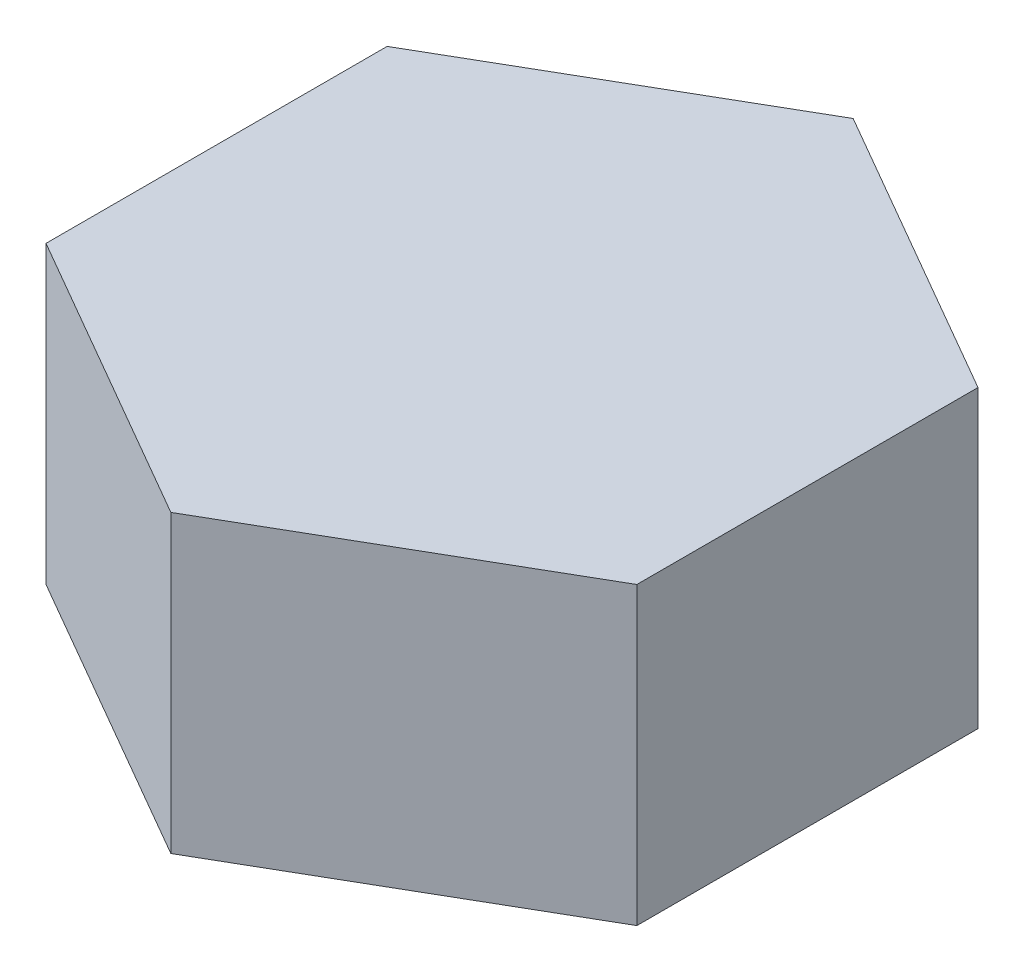
SolidWorks part; units mm, degrees
ref_plane "Front Plane" through (0, 0, 0) normal (0, 0, 1) x (1, 0, 0)
ref_plane "Top Plane" through (0, 0, 0) normal (0, 1, 0) x (1, 0, 0)
ref_plane "Right Plane" through (0, 0, 0) normal (1, 0, 0) x (0, 0, -1)
sketch "Sketch2" plane through (0, 0, 0) normal (0, 1, 0) x (1, 0, 0)
  line L1 (50.8, 29.3294) -> (0, 58.6588)
  line L2 (0, 58.6588) -> (-50.8, 29.3294)
  line L3 (-50.8, 29.3294) -> (-50.8, -29.3294)
  line L4 (-50.8, -29.3294) -> (0, -58.6588)
  line L5 (0, -58.6588) -> (50.8, -29.3294)
  line L6 (50.8, -29.3294) -> (50.8, 29.3294)
  circle A0 centre (0, 0) radius 50.8 construction
extrude "Boss-Extrude2" add sketch "Sketch2" along normal blind 50.8
sketch "Sketch4" plane through (0, 50.8, 0) normal (0, 1, 0) x (1, 0, 0)
  line L0 (0, 58.6588) -> (0, -58.6588)
ref_plane "Plane1" through (0, 0, 0) normal (-1, 0, 0) x (0, 0, 1)
sketch "Sketch13" plane through (0, 50.8, 0) normal (0, 1, 0) x (1, 0, 0)
  line L0 (-50.8, 0) -> (50.8, 0)
  line L1 (-50.8, 29.3294) -> (-50.8, -29.3294) construction
  line L2 (50.8, -29.3294) -> (50.8, 29.3294) construction
  circle A0 centre (0, 0) radius 47.3756
sketch "Sketch14" plane through (0, 0, 0) normal (0, -1, 0) x (-1, 0, 0)
  line L0 (0, -58.6588) -> (0, 58.6588)
sketch "Sketch15" plane through (0, 0, 0) normal (-1, 0, 0) x (0, 0, 1)
  line L0 (-58.6588, 50.8) -> (58.6588, 50.8) construction
  arc A0 (47.2401, 50.8) -> (-47.4979, 50.8) centre (-0.1289, 47.4847) cw
sketch3d "3DSketch2"
  line L0 (50.8, 50.8, 0) -> (-50.8, 50.8, 0) construction
  arc A0 (-46.3664, 50.8, 0) -> (46.3664, 50.8, 0) centre (0, 46.5598, 0) cw
  circle A1 centre (0, 50.8, 0) radius 46.3664 construction
  point P2 (0, 46.5598, 46.5598)
  point P7 (0, 97.1664, 0)
